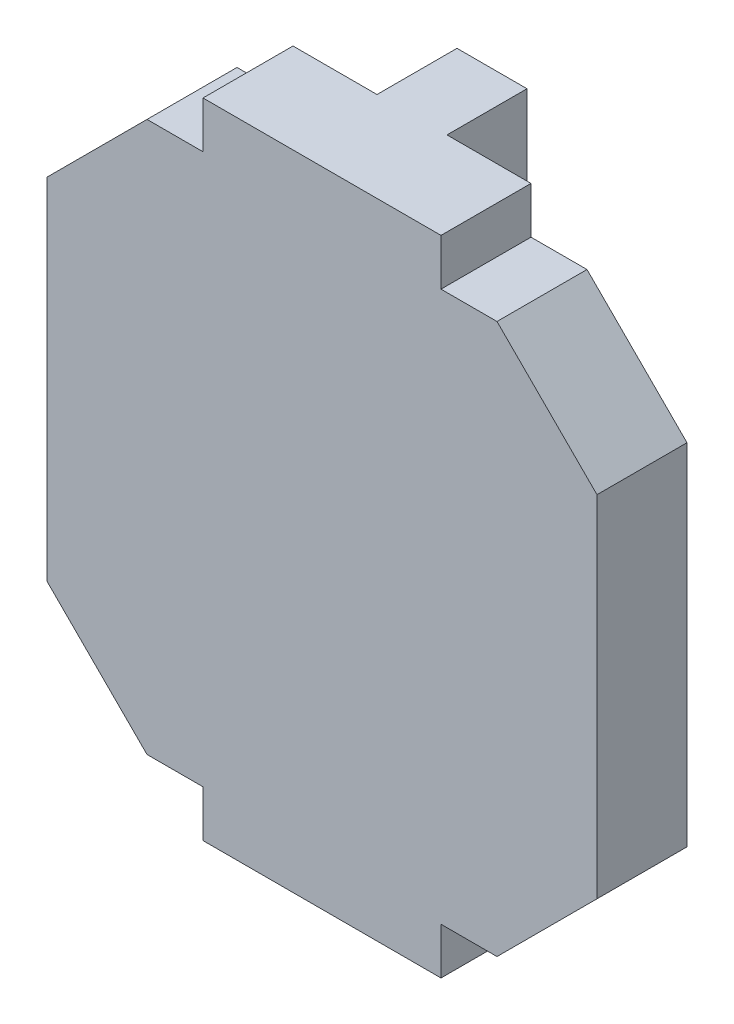
SolidWorks part; units mm, degrees
material "PET"
ref_plane "Front Plane" through (0, 0, 0) normal (0, 0, 1) x (1, 0, 0)
ref_plane "Top Plane" through (0, 0, 0) normal (0, 1, 0) x (1, 0, 0)
ref_plane "Right Plane" through (0, 0, 0) normal (1, 0, 0) x (0, 0, -1)
sketch "Sketch1" plane through (0, 0, 0) normal (0, 0, 1) x (1, 0, 0)
  line L0 (37.0713, 66.6818) -> (39.0525, 66.6818) construction
  line L1 (39.0525, 66.6818) -> (39.0525, 66.0905) construction
  line L5 (39.0525, 74.4106) -> (39.0525, 73.8192) construction
  line L6 (39.0525, 73.8192) -> (37.0713, 73.8192) construction
  line L7 (37.0713, 73.8192) -> (37.0713, 66.6818) construction
  line L8 (44.2087, 73.8192) -> (42.2275, 73.8192) construction
  line L9 (42.2275, 73.8192) -> (42.2275, 74.4106) construction
  line L10 (42.2275, 74.4106) -> (41.148, 74.4106) construction
  line L12 (41.148, 66.0905) -> (42.2275, 66.0905) construction
  line L13 (42.2275, 66.0905) -> (42.2275, 66.6818) construction
  line L14 (42.2275, 66.6818) -> (44.2087, 66.6818) construction
  line L15 (44.2087, 66.6818) -> (44.2087, 73.8192) construction
  line L16 (37.0713, 66.6818) -> (39.0525, 66.6818) construction
  line L17 (39.0525, 66.6818) -> (39.0525, 66.0905) construction
  line L21 (39.0525, 74.4106) -> (39.0525, 73.8192) construction
  line L22 (39.0525, 73.8192) -> (37.0713, 73.8192) construction
  line L23 (37.0713, 73.8192) -> (37.0713, 66.6818) construction
  line L24 (44.2087, 73.8192) -> (42.2275, 73.8192) construction
  line L25 (42.2275, 73.8192) -> (42.2275, 74.4106) construction
  line L26 (42.2275, 74.4106) -> (39.0525, 74.4106) construction
  line L28 (39.0525, 66.0905) -> (42.2275, 66.0905) construction
  line L29 (42.2275, 66.0905) -> (42.2275, 66.6818) construction
  line L30 (42.2275, 66.6818) -> (44.2087, 66.6818) construction
  line L31 (44.2087, 66.6818) -> (44.2087, 73.8192) construction
  line L32 (37.1475, 66.758) -> (39.1287, 66.758)
  line L33 (39.1287, 66.758) -> (39.1287, 66.1667)
  line L34 (39.1287, 66.1667) -> (42.1513, 66.1667)
  line L35 (42.1513, 66.1667) -> (42.1513, 66.758)
  line L36 (42.1513, 66.758) -> (44.1325, 66.758)
  line L37 (44.1325, 66.758) -> (44.1325, 73.743)
  line L38 (44.1325, 73.743) -> (42.1513, 73.743)
  line L39 (42.1513, 73.743) -> (42.1513, 74.3344)
  line L40 (42.1513, 74.3344) -> (39.1287, 74.3344)
  line L41 (39.1287, 74.3344) -> (39.1287, 73.743)
  line L42 (39.1287, 73.743) -> (37.1475, 73.743)
  line L43 (37.1475, 73.743) -> (37.1475, 66.758)
  point P2 (39.1574, 66.0905)
  point P5 (38.9499, 74.4106)
  dimension "D1" = 0.0762
extrude "Boss-Extrude1" add sketch "Sketch1" along normal blind 1.143
sketch "Sketch2" plane through (0, 0, 0) normal (0, 0, -1) x (-1, 0, 0)
  line L0 (-42.1513, 74.3344) -> (-39.1287, 74.3344) construction
  line L1 (-40.1955, 66.0905) -> (-41.0845, 66.0905)
  line L2 (-40.1955, 66.0905) -> (-40.1955, 74.3344)
  line L3 (-40.1955, 74.3344) -> (-41.0845, 74.3344)
  line L4 (-41.0845, 66.0905) -> (-41.0845, 74.3344)
  line L5 (-40.1955, 66.0905) -> (-41.0845, 74.3344) construction
  line L6 (-40.1955, 74.3344) -> (-41.0845, 66.0905) construction
  line L7 (-40.132, 74.4106) -> (-40.132, 66.0905) construction
  line L8 (-41.148, 74.4106) -> (-41.148, 66.0905) construction
  line L9 (-40.132, 66.0905) -> (-41.148, 66.0905) construction
  point P0 (-40.64, 70.2124)
  dimension "D1" = 0.0635
  dimension "D2" = 0.0635
extrude "Boss-Extrude2" add sketch "Sketch2" along normal up to surface (1.016 mm away)
chamfer "Chamfer1" distance 1.27 angle 45 4 edges at (37.1475, 66.758, 0.5715) (44.1325, 66.758, 0.5715) (44.1325, 73.743, 0.5715) (37.1475, 73.743, 0.5715)
